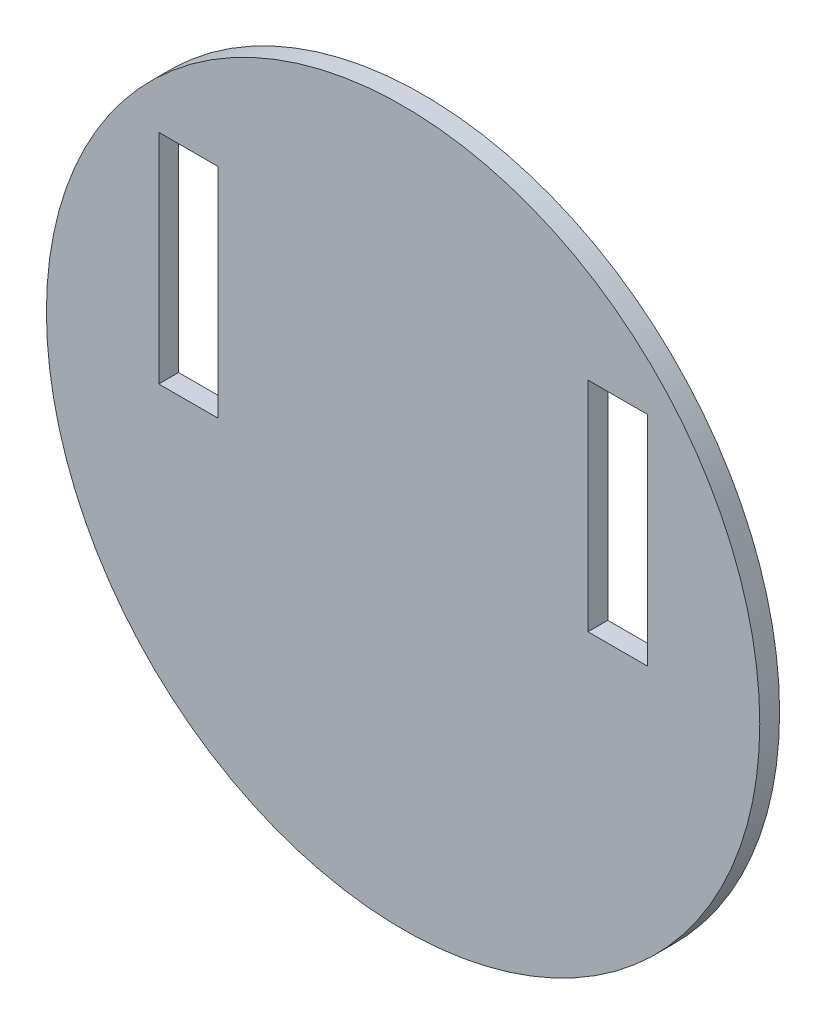
SolidWorks part; units mm, degrees
ref_plane "Front Plane" through (0, 0, 0) normal (0, 0, 1) x (1, 0, 0)
ref_plane "Top Plane" through (0, 0, 0) normal (0, 1, 0) x (1, 0, 0)
ref_plane "Right Plane" through (0, 0, 0) normal (1, 0, 0) x (0, 0, -1)
sketch "Sketch2" plane through (0, 0, 0) normal (0, 0, 1) x (1, 0, 0)
  line L0 (0, 0) -> (99.4495, 0) construction
  line L1 (0, 0) -> (0, 170.256) construction
  line L2 (54.1453, 25.9029) -> (-54.1453, 25.9029) construction
  line L3 (46.6453, -1.5971) -> (61.6453, -1.5971)
  line L4 (46.6453, -1.5971) -> (46.6453, 53.4029)
  line L5 (46.6453, 53.4029) -> (61.6453, 53.4029)
  line L6 (61.6453, -1.5971) -> (61.6453, 53.4029)
  line L7 (46.6453, -1.5971) -> (61.6453, 53.4029) construction
  line L8 (46.6453, 53.4029) -> (61.6453, -1.5971) construction
  line L9 (-61.6453, -1.5971) -> (-46.6453, -1.5971)
  line L10 (-61.6453, -1.5971) -> (-61.6453, 53.4029)
  line L11 (-61.6453, 53.4029) -> (-46.6453, 53.4029)
  line L12 (-46.6453, -1.5971) -> (-46.6453, 53.4029)
  line L13 (-61.6453, -1.5971) -> (-46.6453, 53.4029) construction
  line L14 (-61.6453, 53.4029) -> (-46.6453, -1.5971) construction
  circle A0 centre (0, 0) radius 90
  point P5 (54.1453, 25.9029)
  point P10 (-54.1453, 25.9029)
  point P17 (0, 25.9029)
  point P19 (0, 0)
  dimension "D1" = 180
  dimension "D2" = 55
  dimension "D3" = 15
  dimension "D4" = 108.2906
extrude "Boss-Extrude2" add sketch "Sketch2" along normal blind 5
ref_plane "Plane1" through (0, 0, 5) normal (0, 0, 1) x (1, 0, 0)
